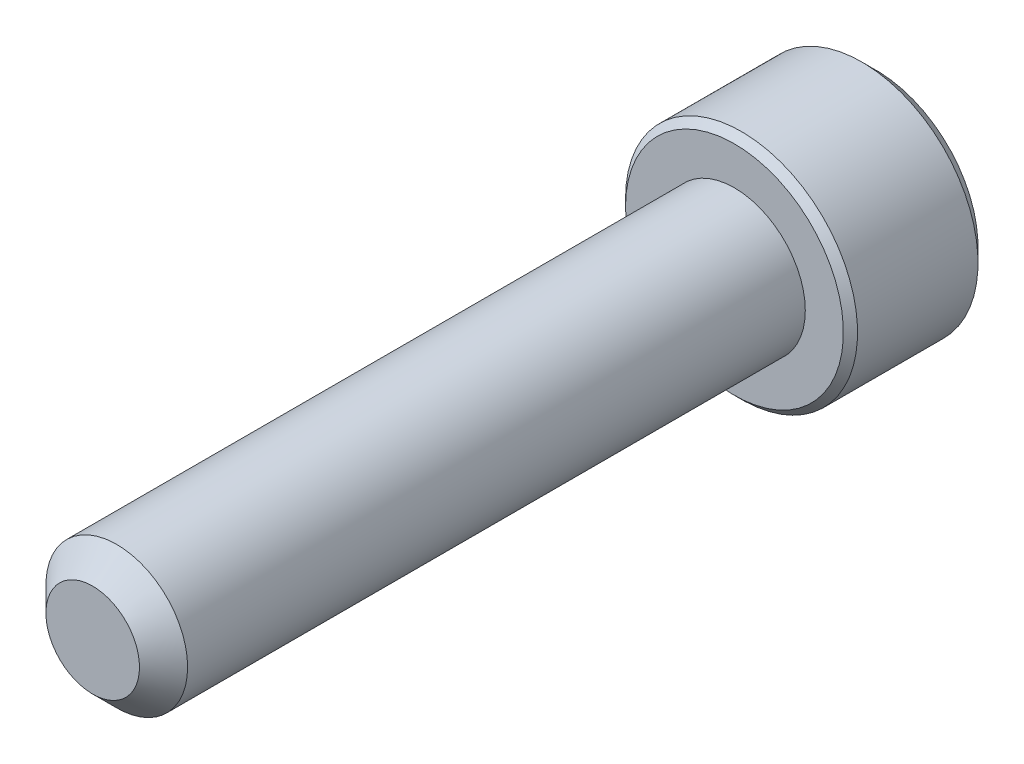
SolidWorks part; units mm, degrees
ref_plane "Front Plane" through (0, 0, 0) normal (0, 0, 1) x (1, 0, 0)
ref_plane "Top Plane" through (0, 0, 0) normal (0, 1, 0) x (1, 0, 0)
ref_plane "Right Plane" through (0, 0, 0) normal (1, 0, 0) x (0, 0, -1)
sketch "Sketch1" plane through (0, 0, 0) normal (0, 0, 1) x (1, 0, 0)
  line L0 (0, 1.7526) -> (0, -1.7526) construction
  circle A0 centre (0, 0) radius 1.7526
  dimension "OD" = 3.5052
extrude "Extrude1" add sketch "Sketch1" against normal blind 15.875
sketch "Sketch2" plane through (0, 0, 0) normal (0, 0, 1) x (1, 0, 0)
  circle A0 centre (0, 0) radius 1.7526 construction
  circle A1 centre (0, 0) radius 1.7526
curve "Helix/Spiral1" pitch 0.7937 height 16.6687 turns 21 parameters "pitch"=0.7937
chamfer "Chamfer3" distance 0.5953 angle 45 1 edges at (1.7526, 0, 0)
sketch "Sketch3" plane through (0, 0, 0) normal (1, 0, 0) x (0, 0, -1)
  line L0 (-0.6945, 1.7526) -> (-0.3969, 1.237)
  line L1 (-0.3969, 1.237) -> (-0.2977, 1.237)
  line L2 (-0.2977, 1.237) -> (0, 1.7526)
  line L3 (-0.6945, 1.7526) -> (0, 1.7526)
  line L4 (-0.3473, 1.7526) -> (-0.3473, 1.237) construction
  line L5 (-0.5457, 1.4948) -> (-0.1488, 1.4948) construction
  line L6 (0, 1.7526) -> (0, -1.7526) construction
  dimension "D1" = 0.0992
  dimension "D2" = 0.3969
  dimension "D3" = 60
sketch "Sketch6" plane through (0, 0, -15.875) normal (0, 0, -1) x (-1, 0, 0)
  circle A0 centre (0, 0) radius 2.8702
  dimension "head dia" = 5.7404
extrude "Extrude2" add sketch "Sketch6" along normal blind 3.5052
sketch "Sketch7" plane through (0, 0, -19.3802) normal (0, 0, -1) x (-1, 0, 0)
  line L1 (0, 1.604) -> (-1.3891, 0.802)
  line L2 (-1.3891, 0.802) -> (-1.3891, -0.802)
  line L3 (-1.3891, -0.802) -> (0, -1.604)
  line L4 (0, -1.604) -> (1.3891, -0.802)
  line L5 (1.3891, -0.802) -> (1.3891, 0.802)
  line L6 (1.3891, 0.802) -> (0, 1.604)
  circle A0 centre (0, 0) radius 1.3891 construction
  dimension "hex dia" = 2.7781
extrude "Cut-Extrude1" cut sketch "Sketch7" against normal blind 2.0836
sketch "Sketch8" plane through (0, 0, -19.3802) normal (0, 0, -1) x (-1, 0, 0)
  circle A0 centre (0, 0) radius 1.604
extrude "Cut-Extrude2" cut sketch "Sketch8" against normal blind 0.3505 draft 45
chamfer "Chamfer1" distance 0.3505 angle 45 1 edges at (-2.8702, 0, -19.3802)
chamfer "Chamfer2" distance 0.1753 angle 45 1 edges at (-2.8702, 0, -15.875)
sketch "Sketch9" plane through (0, 0, 0) normal (1, 0, 0) x (0, 0, -1)
  line L0 (0, 1.7526) -> (0, -1.7526) construction
  line L1 (4.3656, 1.7526) -> (4.3656, -1.7526) construction
  line L2 (15.875, 2.8702) -> (15.875, -2.8702) construction
  line L3 (19.3802, 2.8702) -> (19.3802, -2.8702) construction
  line L4 (19.3802, 0) -> (0, 0) construction
  dimension "D1" = 4.3656
  dimension "D2" = 3.5052
  dimension "D3" = 5.7404
  dimension "D4" = 15.875
equation "\"D3@Helix/Spiral1\" = \"screw length@Extrude1\"+\"pitch@Helix/Spiral1\""
equation "\"D1@Sketch3\" = \"pitch@Helix/Spiral1\"*.125"
equation "\"D2@Sketch3\" = \"pitch@Helix/Spiral1\"*.5"
equation "\"D1@Cut-Extrude1\" = \"hex dia@Sketch7\"*.75"
equation "\"D1@Chamfer1\" = \"head depth@Extrude2\"/10"
equation "\"D1@Sketch9\" = \"pitch@Helix/Spiral1\"*5.5"
equation "\"D1@Chamfer2\" = \"D1@Chamfer1\"/2"
equation "\"D1@Cut-Extrude2\" = \"D1@Chamfer2\"*2"
equation "\"D1@Chamfer3\" = \"pitch@Helix/Spiral1\"*.750"
equation "\"D2@Sketch9\" = \"head depth@Extrude2\""
equation "\"D3@Sketch9\" = \"head dia@Sketch6\""
equation "\"D4@Sketch9\" = \"screw length@Extrude1\""
